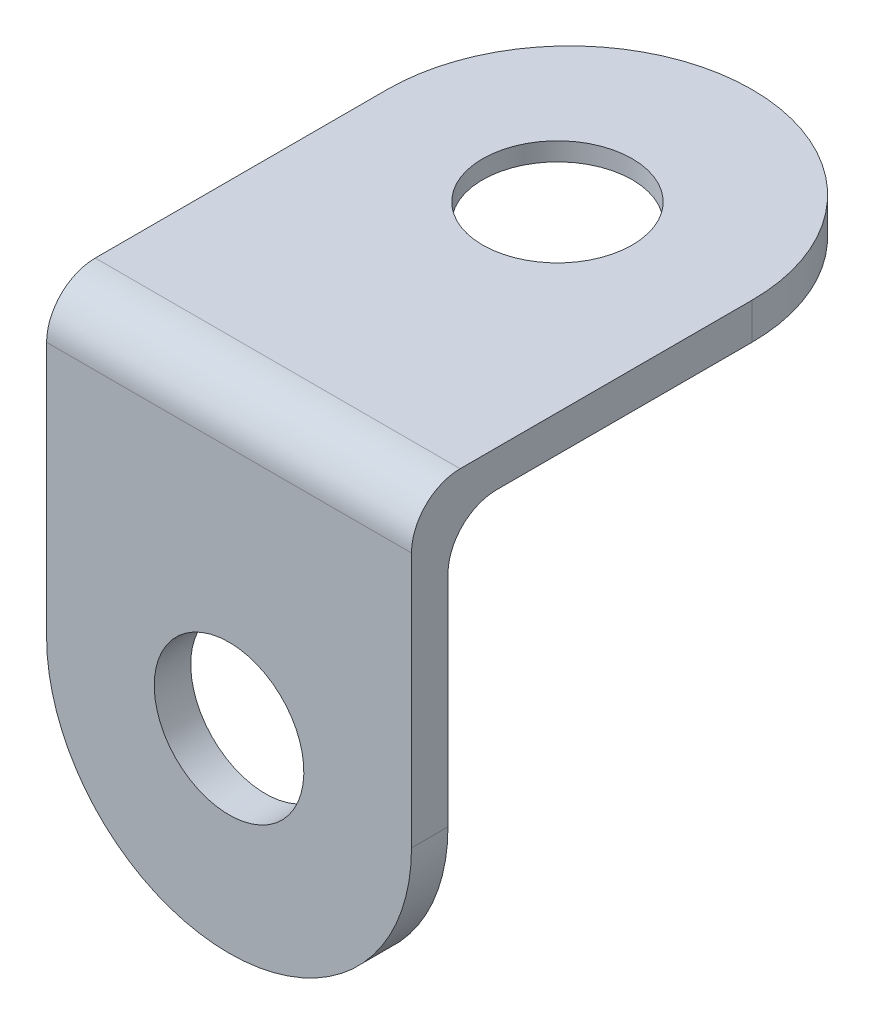
SolidWorks part; units mm, degrees
material "Alloy Steel"
ref_plane "Front Plane" through (0, 0, 0) normal (0, 0, 1) x (1, 0, 0)
ref_plane "Top Plane" through (0, 0, 0) normal (0, 1, 0) x (1, 0, 0)
ref_plane "Right Plane" through (0, 0, 0) normal (1, 0, 0) x (0, 0, -1)
sketch "Sketch1" plane through (0, 0, 0) normal (0, 1, 0) x (1, 0, 0)
  line L0 (-7.5, 0) -> (7.5, 0)
  line L1 (0, 0) -> (0, 20) construction
  line L2 (-7.5, 0) -> (-7.5, 12.5)
  line L3 (7.5, 0) -> (7.5, 12.5)
  arc A0 (7.5, 12.5) -> (-7.5, 12.5) centre (0, 12.5) ccw
  circle A2 centre (0, 12) radius 3.075
  point P4 (0, 0)
  dimension "D5" = 6.15
  dimension "D4" = 8
  dimension "D1" = 15
  dimension "D2" = 20
  dimension "D3" = 12.5
extrude "Boss-Extrude1" add sketch "Sketch1" along normal blind 1.5
ref_plane "Plane1" through (0, 0, 0) normal (0, 0, 1) x (1, 0, 0)
pattern_circular "CirPattern1" count 2 every 90 about axis through (-7.5, 1.5, 0) along (1, 0, 0) of "Boss-Extrude1"
fillet "Fillet1" radius 2 2 edges at (0, 0, 0) (0, 1.5, 1.5)
ref_plane "Plane2" through (0, 0.75, 0) normal (0, -1, 0) x (-1, 0, 0)
sketch "Sketch3" plane through (0, 0.75, 0) normal (0, -1, 0) x (-1, 0, 0)
  circle A0 centre (0, 12) radius 3.075
  dimension "D1" = 6.15
extrude "Cut-Extrude2" cut sketch "Sketch3" along normal up to surface (0.75 mm away) draft 60 contours A0
